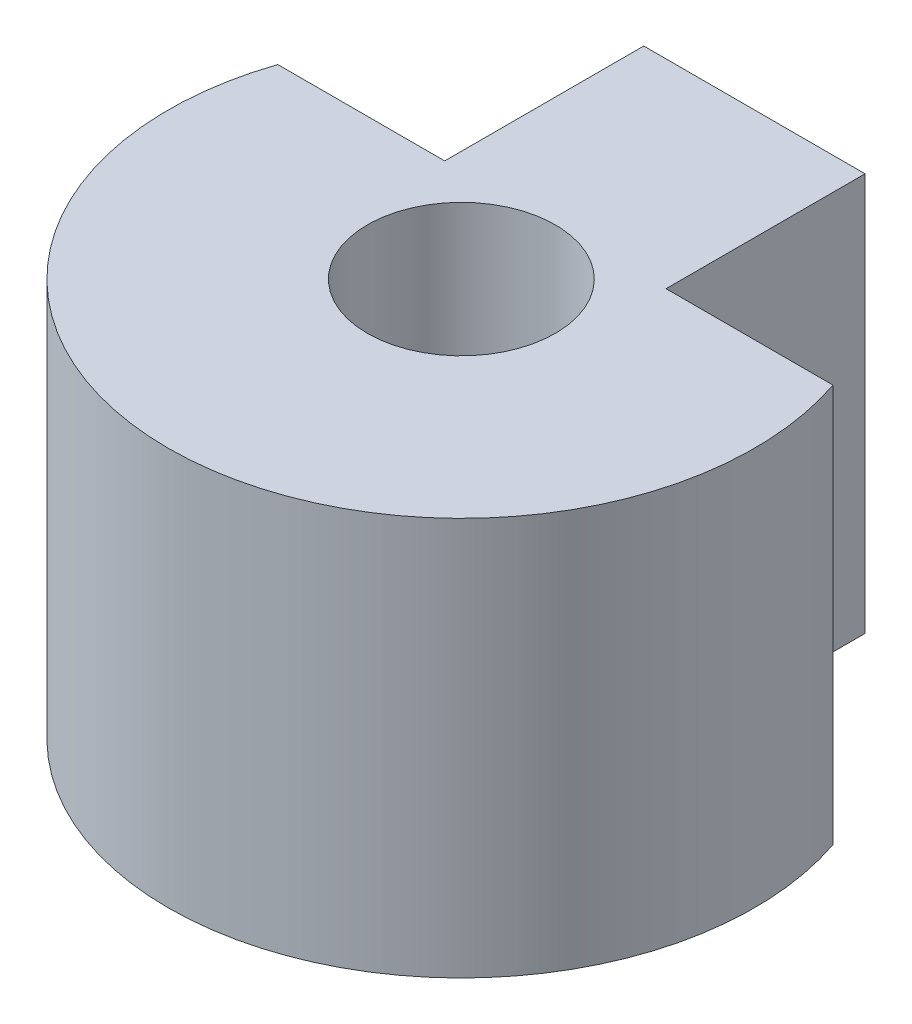
SolidWorks part; units mm, degrees
material "Polyurethane Foam Rigid"
ref_plane "Front Plane" through (0, 0, 0) normal (0, 0, 1) x (1, 0, 0)
ref_plane "Top Plane" through (0, 0, 0) normal (0, 1, 0) x (1, 0, 0)
ref_plane "Right Plane" through (0, 0, 0) normal (1, 0, 0) x (0, 0, -1)
sketch "Sketch1" plane through (0, 0, 0) normal (0, 1, 0) x (1, 0, 0)
  line L0 (0, 4.675) -> (0, 0) construction
  line L2 (-1.7653, 1.5) -> (-1.7653, 4.675)
  line L3 (-1.7653, 4.675) -> (1.7653, 4.675)
  line L4 (1.7653, 1.5) -> (1.7653, 4.675)
  line L5 (-1.7653, 1.5) -> (-4.4278, 1.5)
  line L6 (1.7653, 1.5) -> (4.4278, 1.5)
  circle A0 centre (0, 0) radius 1.5
  arc A1 (-4.4278, 1.5) -> (4.4278, 1.5) centre (0, 0) ccw
  dimension "D1" = 3
  dimension "D2" = 3.175
  dimension "D4" = 3.175
  dimension "D3" = 3.5306
extrude "Boss-Extrude1" add sketch "Sketch1" along normal blind 6.35
